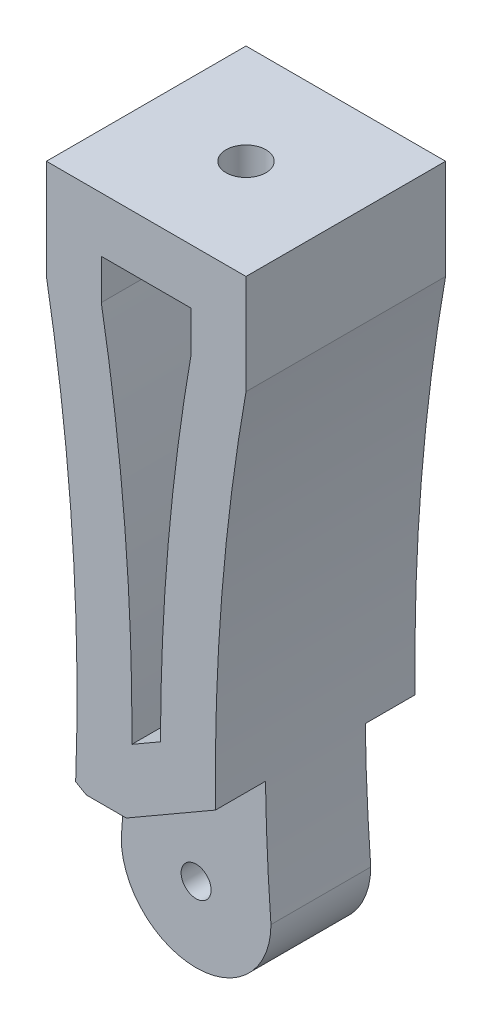
SolidWorks part; units mm, degrees
ref_plane "Front Plane" through (0, 0, 0) normal (0, 0, 1) x (1, 0, 0)
ref_plane "Top Plane" through (0, 0, 0) normal (0, 1, 0) x (1, 0, 0)
ref_plane "Right Plane" through (0, 0, 0) normal (1, 0, 0) x (0, 0, -1)
sketch "Croquis1" plane through (0, 0, 0) normal (0, 0, 1) x (1, 0, 0)
  line L0 (10, 50) -> (10, 60)
  line L1 (10, 60) -> (-10, 60)
  line L2 (-10, 60) -> (-10, 50)
  line L3 (0, 5) -> (-6.9568, 11.8074) construction
  line L6 (0, 5) -> (6.9469, 12.478) construction
  circle A0 centre (0, 0) radius 1.5
  circle A2 centre (0, 50) radius 10 construction
  arc A3 (-10, 50) -> (-7.5, 0) centre (-206.9298, 15.091) cw
  arc A4 (10, 50) -> (7.5, 0) centre (206.9298, 15.091) ccw
  circle A5 centre (0, 0) radius 7.5
  dimension "D1" = 3
  dimension "D3" = 5
  dimension "D4" = 20
  dimension "D5" = 200
  dimension "D6" = 200
  dimension "D7" = 15
  dimension "D2" = 60
extrude "Saliente-Extruir1" add sketch "Croquis1" along normal blind 20 contours A5 A4 L0 L1 L2 A3 | A4 A5 A3 A0
sketch "Croquis2" plane through (0, 0, 20) normal (0, 0, 1) x (1, 0, 0)
  line L0 (-7.0695, 7.6175) -> (-6, 7)
  line L1 (-6, 7) -> (-2, 7)
  line L2 (-2, 7) -> (6.9512, 12.168)
  arc A0 (10, 50) -> (7.5, 0) centre (206.9298, 15.091) ccw construction
  arc A1 (-7.5, 0) -> (-10, 50) centre (-206.9298, 15.091) ccw construction
  arc A2 (-7.5, 0) -> (7.5, 0) centre (0, 0) ccw construction
  arc A3 (6.9512, 12.168) -> (7.5, 0) centre (206.9298, 15.091) ccw
  arc A4 (-7.5, 0) -> (7.5, 0) centre (0, 0) ccw
  arc A5 (-7.5, 0) -> (-7.0695, 7.6175) centre (-206.9298, 15.091) ccw
  arc A6 (-7.5, 0) -> (-10, 50) centre (-206.9298, 15.091) ccw construction
  dimension "D1" = 7
  dimension "D2" = 30
  dimension "D3" = 30
  dimension "D4" = 4
  dimension "D5" = 2
extrude "Cortar-Extruir1" cut sketch "Croquis2" against normal blind 5
sketch "Croquis3" plane through (0, 0, 0) normal (0, 0, -1) x (-1, 0, 0)
  line L0 (-6.9512, 12.168) -> (2, 7)
  line L1 (2, 7) -> (6, 7)
  line L2 (6, 7) -> (7.0695, 7.6175)
  arc A0 (-7.5, 0) -> (-10, 50) centre (-206.9298, 15.091) ccw construction
  arc A1 (10, 50) -> (7.5, 0) centre (206.9298, 15.091) ccw construction
  arc A2 (-7.5, 0) -> (7.5, 0) centre (0, 0) ccw construction
  arc A3 (7.0695, 7.6175) -> (7.5, 0) centre (206.9298, 15.091) ccw
  arc A4 (-7.5, 0) -> (7.5, 0) centre (0, 0) ccw
  arc A5 (-7.5, 0) -> (-6.9512, 12.168) centre (-206.9298, 15.091) ccw
  dimension "D1" = 7
  dimension "D2" = 30
  dimension "D3" = 30
  dimension "D4" = 4
  dimension "D5" = 2
extrude "Cortar-Extruir2" cut sketch "Croquis3" against normal blind 5
sketch "Croquis4" plane through (0, 0, 20) normal (0, 0, 1) x (1, 0, 0)
  line L8 (-1.4347, 13.6772) -> (1.43, 15.3312)
  line L9 (-1.4347, 13.6772) -> (1.43, 15.3312)
  line L15 (4.5, 50.4804) -> (4.5, 54.5)
  line L16 (4.5, 54.5) -> (-4.5, 54.5)
  line L17 (-4.5, 54.5) -> (-4.5, 50.4804)
  line L21 (4.5, 50.4804) -> (4.5, 54.5)
  line L22 (4.5, 54.5) -> (-4.5, 54.5)
  line L23 (-4.5, 54.5) -> (-4.5, 50.4804)
  arc A4 (4.5, 50.4804) -> (1.43, 15.3312) centre (206.9298, 15.091) ccw
  arc A5 (-1.4347, 13.6772) -> (-4.5, 50.4804) centre (-206.9298, 15.091) ccw
  arc A6 (4.5, 50.4804) -> (1.43, 15.3312) centre (206.9298, 15.091) ccw
  arc A7 (-1.4347, 13.6772) -> (-4.5, 50.4804) centre (-206.9298, 15.091) ccw
  point P0 (-1.4347, 13.6772)
  dimension "D1" = 5.5
extrude "Cortar-Extruir3" cut sketch "Croquis4" against normal through all
sketch "Croquis5" plane through (0, 60, 0) normal (0, 1, 0) x (1, 0, 0)
  line L0 (-10, -20) -> (-10, 0) construction
  circle A0 centre (0, -10) radius 2
  point P6 (-10, -10)
  dimension "D1" = 4
extrude "Cortar-Extruir4" cut sketch "Croquis5" against normal blind 10
